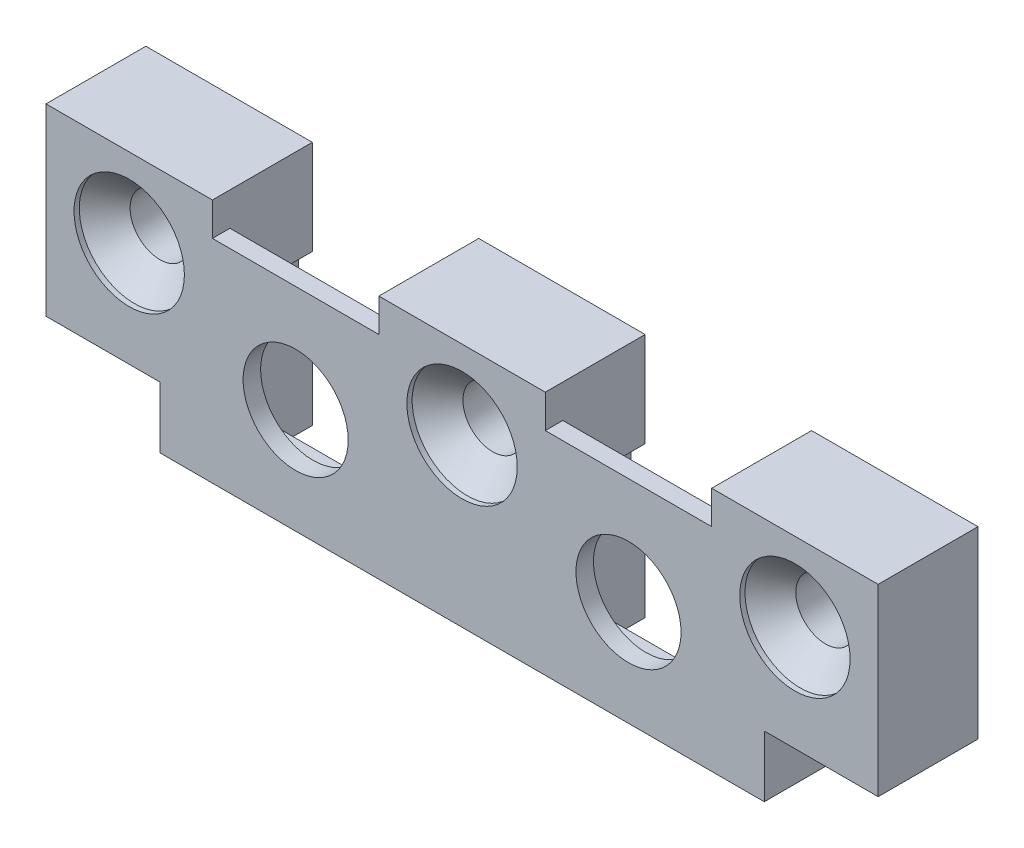
SolidWorks part; units mm, degrees
ref_plane "Front Plane" through (0, 0, 0) normal (0, 0, 1) x (1, 0, 0)
ref_plane "Top Plane" through (0, 0, 0) normal (0, 1, 0) x (1, 0, 0)
ref_plane "Right Plane" through (0, 0, 0) normal (1, 0, 0) x (0, 0, -1)
sketch "Sketch1" plane through (0, 0, 0) normal (0, 0, 1) x (1, 0, 0)
  line L0 (-54.75, 14) -> (-64.25, 14)
  line L1 (-81, 14) -> (-54.75, 14) construction
  line L2 (-64.25, 14) -> (-64.25, 0)
  line L3 (-3, 0) -> (-26.25, 0) construction
  line L4 (-64.25, 0) -> (-54.75, 0)
  line L5 (-16.75, 0) -> (-16.75, 14)
  line L6 (-26.25, 14) -> (0, 14) construction
  line L7 (-16.75, 14) -> (-26.25, 14)
  line L8 (-26.25, 14) -> (-26.25, 8.6)
  line L9 (-26.25, 8.6) -> (-25.45, 8.6)
  line L10 (-25.45, 8.6) -> (-25.45, 4.6)
  line L11 (-25.45, 4.6) -> (-26.25, 4.6)
  line L12 (-26.25, 4.6) -> (-26.25, 0)
  line L14 (-35.75, 0) -> (-35.75, 4.6)
  line L15 (-35.75, 4.6) -> (-36.55, 4.6)
  line L16 (-36.55, 4.6) -> (-36.55, 8.6)
  line L17 (-36.55, 8.6) -> (-35.75, 8.6)
  line L18 (-35.75, 8.6) -> (-35.75, 14)
  line L19 (-35.75, 14) -> (-45.25, 14)
  line L20 (-45.25, 14) -> (-45.25, 8.6)
  line L21 (-45.25, 8.6) -> (-44.45, 8.6)
  line L22 (-44.45, 8.6) -> (-44.45, 4.6)
  line L23 (-44.45, 4.6) -> (-45.25, 4.6)
  line L24 (-45.25, 4.6) -> (-45.25, 0)
  line L26 (-54.75, 0) -> (-54.75, 4.6)
  line L27 (-54.75, 4.6) -> (-55.55, 4.6)
  line L28 (-55.55, 4.6) -> (-55.55, 8.6)
  line L29 (-55.55, 8.6) -> (-54.75, 8.6)
  line L30 (-54.75, 8.6) -> (-54.75, 14)
  line L31 (-45.25, 0) -> (-35.75, 0)
  line L32 (-26.25, 0) -> (-16.75, 0)
  circle A0 centre (-40.5, 9.5) radius 1.5
  circle A1 centre (-21.5, 9.5) radius 1.5
  circle A2 centre (-59.5, 9.5) radius 1.5
  dimension "D1" = 0.8
  dimension "D2" = 9.5
extrude "Boss-Extrude1" add sketch "Sketch1" along normal up to surface (1.2 mm away) contours L29 L30 L0 L2 L4 L26 L27 L28 A2 | L24 L31 L14 L15 L16 L17 L18 L19 L20 L21 L22 L23 A0 | L12 L32 L5 L7 L8 L9 L10 L11 A1
sketch "Sketch2" plane through (0, 0, 1.2) normal (0, 0, 1) x (1, 0, 0)
  line L0 (-54.75, 14) -> (-64.25, 14)
  line L1 (-64.25, 14) -> (-64.25, 0)
  line L2 (-64.25, 0) -> (-16.75, 0)
  line L3 (-16.75, 0) -> (-16.75, 14)
  line L4 (-16.75, 14) -> (-26.25, 14)
  line L10 (-26.25, 1.1) -> (-35.75, 1.1)
  line L16 (-35.75, 14) -> (-45.25, 14)
  line L22 (-45.25, 1.1) -> (-54.75, 1.1)
  line L28 (-54.75, 14) -> (-54.75, 1.1)
  line L29 (-45.25, 14) -> (-45.25, 1.1)
  line L30 (-35.75, 14) -> (-35.75, 1.1)
  line L31 (-26.25, 14) -> (-26.25, 1.1)
  line L32 (-47.25, 1.1) -> (-52.75, 1.1) construction
  circle A0 centre (-59.5, 9.5) radius 1.5
  circle A1 centre (-40.5, 9.5) radius 1.5
  circle A2 centre (-21.5, 9.5) radius 1.5
extrude "Boss-Extrude2" add sketch "Sketch2" along normal up to surface (3.5 mm away)
sketch "Sketch3" plane through (0, 0, 4.7) normal (0, 0, 1) x (1, 0, 0)
  line L0 (-64.25, 14) -> (-54.75, 14)
  line L1 (-54.75, 14) -> (-54.75, 12.1)
  line L2 (-54.75, 12.1) -> (-45.25, 12.1)
  line L3 (-45.25, 12.1) -> (-45.25, 14)
  line L4 (-45.25, 14) -> (-35.75, 14)
  line L5 (-35.75, 14) -> (-35.75, 12.1)
  line L6 (-35.75, 12.1) -> (-26.25, 12.1)
  line L7 (-26.25, 12.1) -> (-26.25, 14)
  line L8 (-26.25, 14) -> (-16.75, 14)
  line L9 (-16.75, 14) -> (-16.75, 0)
  line L10 (-16.75, 0) -> (-64.25, 0)
  line L11 (-64.25, 0) -> (-64.25, 14)
  line L12 (-64.25, 0) -> (-16.75, 0) construction
  circle A0 centre (-59.5, 9.5) radius 1.5
  circle A1 centre (-40.5, 9.5) radius 1.5
  circle A2 centre (-21.5, 9.5) radius 1.5
extrude "Boss-Extrude3" add sketch "Sketch3" along normal blind 1
hole_wizard "CSK for M3 Countersunk Flat Head Screw1" positions "Sketch4" profile "Sketch6" countersink size "M3" standard "ISO" end condition through all
sketch "Sketch4" plane through (0, 0, 5.7) normal (0, 0, 1) x (1, 0, 0)
  point P0 (-59.5, 9.5)
  point P3 (-59.5, 9.5)
  point P6 (-40.5, 9.5)
  point P9 (-21.5, 9.5)
sketch "Sketch6" plane through (-59.5, 9.5, 5.7) normal (1, 0, 0) x (0, -1, 0)
  line L0 (0, 0) -> (0, 5.7)
  line L1 (0, 5.7) -> (1.7, 5.7)
  line L2 (1.7, 5.7) -> (1.7, 1.75)
  line L3 (1.7, 1.75) -> (3.15, 0.3)
  line L4 (3.15, 0.3) -> (3.15, 0)
  line L6 (3.15, 0) -> (0, 0)
  line L7 (-1.7, 1.75) -> (-3.15, 0.3) construction
  line L11 (0, -6.35) -> (0, 107.95) construction
  dimension "Thru Hole Dia." = 3.4
  dimension "Thru Hole Depth" = 5.7
  dimension "C'Sink Dia." = 6.3
  dimension "C'Sink Angle" = 90
  dimension "Head Clearance" = 0.3
sketch "Sketch7" plane through (0, 0, 5.7) normal (0, 0, 1) x (1, 0, 0)
  circle A0 centre (-50, 6) radius 3
  circle A1 centre (-31, 6) radius 3
  dimension "D1" = 6
extrude "Cut-Extrude1" cut sketch "Sketch7" against normal through all
sketch "Sketch8" plane through (0, 0, 5.7) normal (0, 0, 1) x (1, 0, 0)
  line L1 (-64.25, 0) -> (-57.75, 0)
  line L2 (-64.25, 0) -> (-64.25, 3.5)
  line L3 (-64.25, 3.5) -> (-57.75, 3.5)
  line L4 (-57.75, 0) -> (-57.75, 3.5)
  line L5 (-16.75, 0) -> (-23.25, 0)
  line L6 (-16.75, 0) -> (-16.75, 3.5)
  line L7 (-16.75, 3.5) -> (-23.25, 3.5)
  line L8 (-23.25, 0) -> (-23.25, 3.5)
  dimension "D1" = 34.5
  dimension "D2" = 3.5
extrude "Cut-Extrude2" cut sketch "Sketch8" against normal through all
sketch "Sketch10" plane through (0, 0, 1.2) normal (0, 0, -1) x (-1, 0, 0)
  line L1 (26.25, 1.1) -> (35.75, 1.1)
  line L2 (26.25, 1.1) -> (26.25, 0)
  line L3 (26.25, 0) -> (35.75, 0)
  line L4 (35.75, 1.1) -> (35.75, 0)
  line L5 (45.25, 0) -> (54.75, 0)
  line L6 (45.25, 0) -> (45.25, 1.1)
  line L7 (45.25, 1.1) -> (54.75, 1.1)
  line L8 (54.75, 0) -> (54.75, 1.1)
extrude "Cut-Extrude3" cut sketch "Sketch10" against normal blind 1
